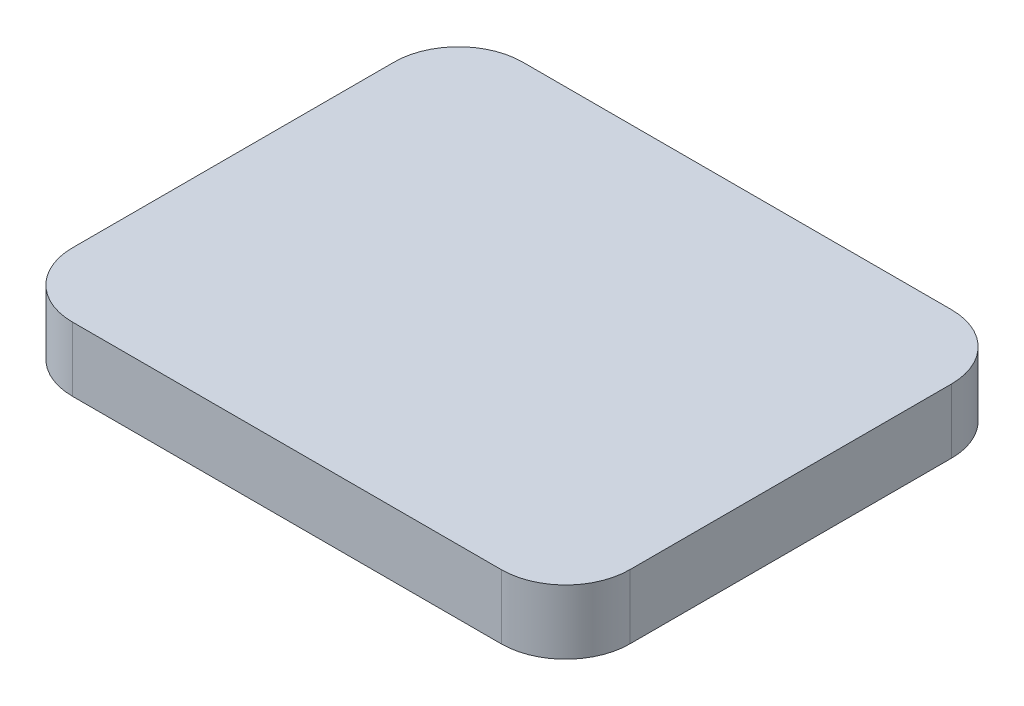
SolidWorks part; units mm, degrees
ref_plane "Front Plane" through (0, 0, 0) normal (0, 0, 1) x (1, 0, 0)
ref_plane "Top Plane" through (0, 0, 0) normal (0, 1, 0) x (1, 0, 0)
ref_plane "Right Plane" through (0, 0, 0) normal (1, 0, 0) x (0, 0, -1)
sketch "Sketch1" plane through (0, 0, 0) normal (0, 1, 0) x (1, 0, 0)
  line L0 (-100, 105) -> (100, 105)
  line L5 (130, 0) -> (-130, 0) construction
  line L6 (0, 105) -> (0, -105) construction
  line L11 (-130, 75) -> (-130, -75)
  line L12 (-100, -105) -> (100, -105)
  line L13 (130, 75) -> (130, -75)
  line L28 (-100.5277, 0) -> (100.5277, 0) construction
  line L29 (0, 75.8803) -> (0, -71.7803) construction
  arc A0 (100, 105) -> (130, 75) centre (100, 75) cw
  arc A1 (-100, 105) -> (-130, 75) centre (-100, 75) ccw
  arc A2 (-130, -75) -> (-100, -105) centre (-100, -75) ccw
  arc A3 (100, -105) -> (130, -75) centre (100, -75) ccw
  point P0 (0, 0)
  point P18 (0, 0)
  point P53 (0, 0)
  dimension "D3" = 30
  dimension "D1" = 150
  dimension "D2" = 200
extrude "Boss-Extrude2" add sketch "Sketch1" along normal blind 30
